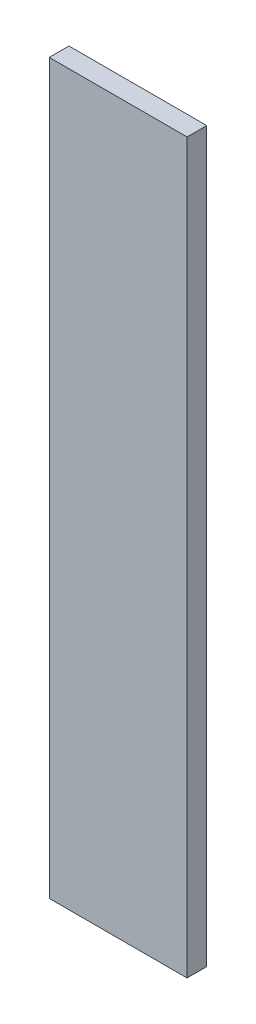
SolidWorks part; units mm, degrees
ref_plane "Front Plane" through (0, 0, 0) normal (0, 0, 1) x (1, 0, 0)
ref_plane "Top Plane" through (0, 0, 0) normal (0, 1, 0) x (1, 0, 0)
ref_plane "Right Plane" through (0, 0, 0) normal (1, 0, 0) x (0, 0, -1)
sketch "Sketch1" plane through (0, 0, 0) normal (0, 0, 1) x (1, 0, 0)
  line L0 (0, 0) -> (70, 0)
  line L1 (70, 0) -> (70, -370)
  line L2 (70, -370) -> (0, -370)
  line L3 (0, -370) -> (0, 0)
  dimension "D1" = 370
  dimension "D2" = 70
extrude "Boss-Extrude1" add sketch "Sketch1" along normal blind 10
